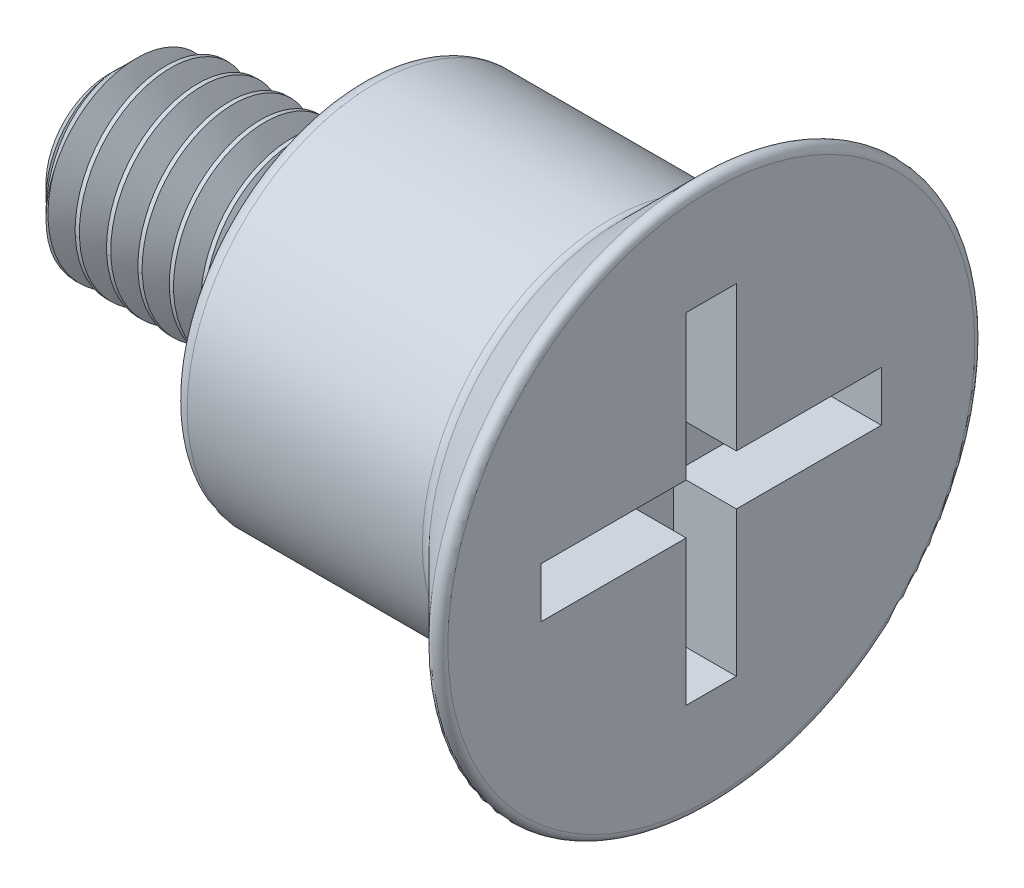
SolidWorks part; units mm, degrees
ref_plane "Front Plane" through (0, 0, 0) normal (0, 0, 1) x (1, 0, 0)
ref_plane "Top Plane" through (0, 0, 0) normal (0, 1, 0) x (1, 0, 0)
ref_plane "Right Plane" through (0, 0, 0) normal (1, 0, 0) x (0, 0, -1)
sketch "Sketch1" plane through (0, 0, 0) normal (0, 0, 1) x (1, 0, 0)
  line L0 (0, 0) -> (0, 4.5)
  line L2 (0, 4.5) -> (-1.5, 3)
  line L3 (-1.5, 3) -> (-5.6, 3)
  line L4 (-5.6, 3) -> (-5.6, 1.5)
  line L5 (-5.6, 1.5) -> (-9.6, 1.5)
  line L6 (-9.6, 1.5) -> (-9.6, 0)
  line L7 (-9.6, 0) -> (0, 0)
  line L8 (-26.7311, 0) -> (12124.8688, 0) construction
  dimension "D1" = 3
  dimension "D2" = 6
  dimension "D3" = 4
  dimension "D4" = 45
  dimension "D5" = 9
  dimension "D6" = 5.6
revolve "Revolve1" add sketch "Sketch1" angle 360 about L8
sketch "Sketch2" plane through (0, 0, 0) normal (1, 0, 0) x (0, 0, -1)
  line L1 (0.4, -2.7096) -> (-0.4, -2.7096)
  line L2 (0.4, -2.7096) -> (0.4, 2.7096)
  line L3 (0.4, 2.7096) -> (-0.4, 2.7096)
  line L4 (-0.4, -2.7096) -> (-0.4, 2.7096)
  line L5 (0.4, -2.7096) -> (-0.4, 2.7096) construction
  line L6 (0.4, 2.7096) -> (-0.4, -2.7096) construction
  line L7 (-2.7096, 0.4) -> (2.7096, 0.4)
  line L8 (-2.7096, 0.4) -> (-2.7096, -0.4)
  line L9 (-2.7096, -0.4) -> (2.7096, -0.4)
  line L10 (2.7096, 0.4) -> (2.7096, -0.4)
  line L11 (-2.7096, 0.4) -> (2.7096, -0.4) construction
  line L12 (-2.7096, -0.4) -> (2.7096, 0.4) construction
  point P0 (0, 0)
  point P6 (0, 0)
  dimension "D1" = 0.8
extrude "Cut-Extrude1" cut sketch "Sketch2" against normal blind 1 contours L4 L7 L2 L3 | L4 L9 L2 L7 | L10 L7 L2 L9 | L8 L9 L4 L7 | L9 L4 L1 L2
chamfer "Chamfer1" distance 0.5 angle 45 1 edges at (-9.6, 0, 1.5)
fillet "Fillet1" radius 0.25 2 edges at (-1.5, 0, 3) (-5.6, 0, 3)
fillet "Fillet2" radius 0.125 1 edges at (0, 0, 4.5)
sketch "Sketch3" plane through (-9.6, 0, 0) normal (-1, 0, 0) x (0, 0, 1)
  circle A0 centre (0, 0) radius 1.125
  dimension "D1" = 2.25
curve "Helix/Spiral1" pitch 0.5 height 3.5 turns 7
sketch "Sketch4" plane through (0, 0, 0) normal (0, 1, 0) x (1, 0, 0)
  line L0 (-9.8266, 1.5175) -> (-9.3734, 1.5175)
  line L1 (-9.3734, 1.5175) -> (-9.6, 1.125)
  line L2 (-9.6, 1.125) -> (-9.8266, 1.5175)
  spline S0 degree 3 poles (-9.6, 1.125) (-9.5896, 1.125) (-9.5687, 1.0664) (-9.5375, 0.8162) (-9.5062, 0.4417) (-9.475, 0) (-9.4437, -0.4417) (-9.4125, -0.8162) (-9.3812, -1.0664) (-9.35, -1.1543) (-9.3187, -1.0664) (-9.2875, -0.8162) (-9.2562, -0.4417) (-9.225, 0) (-9.1937, 0.4417) (-9.1625, 0.8162) (-9.1312, 1.0664) (-9.1, 1.1543) (-9.0687, 1.0664) (-9.0375, 0.8162) (-9.0062, 0.4417) (-8.975, 0) (-8.9437, -0.4417) (-8.9125, -0.8162) (-8.8813, -1.0664) (-8.85, -1.1543) (-8.8188, -1.0664) (-8.7875, -0.8162) (-8.7562, -0.4417) (-8.725, 0) (-8.6937, 0.4417) (-8.6625, 0.8162) (-8.6312, 1.0664) (-8.6, 1.1543) (-8.5687, 1.0664) (-8.5375, 0.8162) (-8.5062, 0.4417) (-8.475, 0) (-8.4437, -0.4417) (-8.4125, -0.8162) (-8.3812, -1.0664) (-8.35, -1.1543) (-8.3187, -1.0664) (-8.2875, -0.8162) (-8.2562, -0.4417) (-8.225, 0) (-8.1937, 0.4417) (-8.1625, 0.8162) (-8.1312, 1.0664) (-8.1, 1.1543) (-8.0687, 1.0664) (-8.0375, 0.8162) (-8.0062, 0.4417) (-7.975, 0) (-7.9437, -0.4417) (-7.9125, -0.8162) (-7.8812, -1.0664) (-7.85, -1.1543) (-7.8187, -1.0664) (-7.7875, -0.8162) (-7.7562, -0.4417) (-7.725, 0) (-7.6937, 0.4417) (-7.6625, 0.8162) (-7.6312, 1.0664) (-7.6, 1.1543) (-7.5687, 1.0664) (-7.5375, 0.8162) (-7.5062, 0.4417) (-7.475, 0) (-7.4437, -0.4417) (-7.4125, -0.8162) (-7.3812, -1.0664) (-7.35, -1.1543) (-7.3187, -1.0664) (-7.2875, -0.8162) (-7.2562, -0.4417) (-7.225, 0) (-7.1937, 0.4417) (-7.1625, 0.8162) (-7.1312, 1.0664) (-7.1, 1.1543) (-7.0687, 1.0664) (-7.0375, 0.8162) (-7.0062, 0.4417) (-6.975, 0) (-6.9437, -0.4417) (-6.9125, -0.8162) (-6.8812, -1.0664) (-6.85, -1.1543) (-6.8187, -1.0664) (-6.7875, -0.8162) (-6.7563, -0.4417) (-6.725, 0) (-6.6937, 0.4417) (-6.6625, 0.8162) (-6.6313, 1.0664) (-6.6, 1.1543) (-6.5688, 1.0664) (-6.5375, 0.8162) (-6.5063, 0.4417) (-6.475, 0) (-6.4438, -0.4417) (-6.4125, -0.8162) (-6.3813, -1.0664) (-6.35, -1.1543) (-6.3188, -1.0664) (-6.2875, -0.8162) (-6.2563, -0.4417) (-6.225, 0) (-6.1938, 0.4417) (-6.1625, 0.8162) (-6.1313, 1.0664) (-6.1104, 1.125) (-6.1, 1.125) knots 0 0 0 0 0.008929 0.017857 0.026786 0.035714 0.044643 0.053571 0.0625 0.071429 0.080357 0.089286 0.098214 0.107143 0.116071 0.125 0.133929 0.142857 0.151786 0.160714 0.169643 0.178571 0.1875 0.196429 0.205357 0.214286 0.223214 0.232143 0.241071 0.25 0.258929 0.267857 0.276786 0.285714 0.294643 0.303571 0.3125 0.321429 0.330357 0.339286 0.348214 0.357143 0.366071 0.375 0.383929 0.392857 0.401786 0.410714 0.419643 0.428571 0.4375 0.446429 0.455357 0.464286 0.473214 0.482143 0.491071 0.5 0.508929 0.517857 0.526786 0.535714 0.544643 0.553571 0.5625 0.571429 0.580357 0.589286 0.598214 0.607143 0.616071 0.625 0.633929 0.642857 0.651786 0.660714 0.669643 0.678571 0.6875 0.696429 0.705357 0.714286 0.723214 0.732143 0.741071 0.75 0.758929 0.767857 0.776786 0.785714 0.794643 0.803571 0.8125 0.821429 0.830357 0.839286 0.848214 0.857143 0.866071 0.875 0.883929 0.892857 0.901786 0.910714 0.919643 0.928571 0.9375 0.946429 0.955357 0.964286 0.973214 0.982143 0.991071 1 1 1 1 construction
  dimension "D1" = 60
  dimension "D2" = 60
sweep "Cut-Sweep1" cut profiles "Sketch4" path "Helix/Spiral1"
